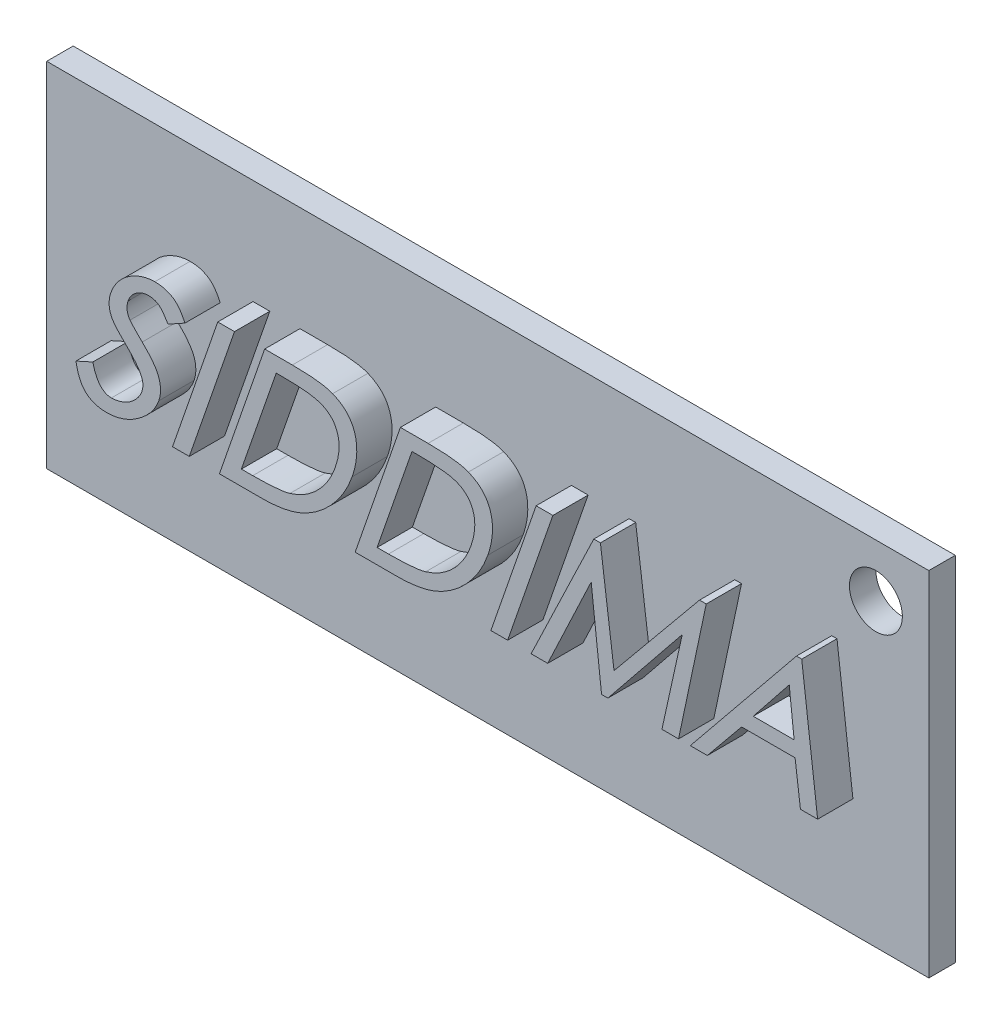
SolidWorks part; units mm, degrees
ref_plane "Front Plane" through (0, 0, 0) normal (0, 0, 1) x (1, 0, 0)
ref_plane "Top Plane" through (0, 0, 0) normal (0, 1, 0) x (1, 0, 0)
ref_plane "Right Plane" through (0, 0, 0) normal (1, 0, 0) x (0, 0, -1)
sketch "Sketch1" plane through (0, 0, 0) normal (0, 0, 1) x (1, 0, 0)
  line L1 (-25, -10) -> (25, -10)
  line L2 (-25, -10) -> (-25, 10)
  line L3 (-25, 10) -> (25, 10)
  line L4 (25, -10) -> (25, 10)
  line L5 (-25, -10) -> (25, 10) construction
  line L6 (-25, 10) -> (25, -10) construction
  point P0 (0, 0)
  dimension "D1" = 20
  dimension "D2" = 50
extrude "Boss-Extrude1" add sketch "Sketch1" along normal blind 1.5
sketch "Sketch2" plane through (0, 0, 1.5) normal (0, 0, 1) x (1, 0, 0)
  text T0 "SIDDIMA" font "Century Gothic" height in points 28
extrude "Boss-Extrude2" add sketch "Sketch2" along normal blind 2
sketch "Sketch3" plane through (0, 0, 1.5) normal (0, 0, 1) x (1, 0, 0)
  line L0 (25, -10) -> (25, 10) construction
  line L1 (25, 10) -> (-25, 10) construction
  circle A0 centre (22, 7) radius 1.5
  dimension "D1" = 3
  dimension "D2" = 3
  dimension "D3" = 3
extrude "Cut-Extrude1" cut sketch "Sketch3" against normal blind 2
